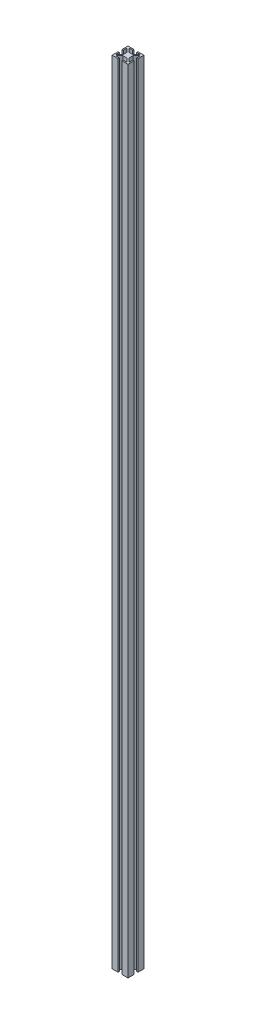
SolidWorks part; units mm, degrees
ref_plane "Plan de face" through (0, 0, 0) normal (0, 0, 1) x (1, 0, 0)
ref_plane "Plan de dessus" through (0, 0, 0) normal (0, 1, 0) x (1, 0, 0)
ref_plane "Plan de droite" through (0, 0, 0) normal (1, 0, 0) x (0, 0, -1)
sketch "Esquisse1" plane through (0, 0, 0) normal (0, 1, 0) x (1, 0, 0)
  line L0 (6.1245, 16.1036) -> (30.6226, 16.1036) construction
  line L6 (-11.5924, 0) -> (12.1076, 0) construction
  line L7 (0, 12.3466) -> (0, -12.7449) construction
  line L12 (-10, -10) -> (10, 10) construction
  line L59 (-10, -2.5) -> (-10, -10)
  line L60 (-10, -2.5) -> (-8.5, -2.5)
  line L69 (-8.5, -2.5) -> (-8.5, -6.2322)
  line L70 (-7.6464, -6.5858) -> (-3.75, -2.6893)
  line L73 (-6.5858, -7.6464) -> (-2.6893, -3.75)
  line L74 (-2.5, -8.5) -> (-6.2322, -8.5)
  line L75 (-2.5, -10) -> (-2.5, -8.5)
  line L76 (-2.5, -10) -> (-10, -10)
  line L77 (-2.5, 10) -> (-2.5, 8.5)
  line L78 (-2.5, 10) -> (-10, 10)
  line L79 (-10, 2.5) -> (-10, 10)
  line L80 (-10, 2.5) -> (-8.5, 2.5)
  line L81 (-8.5, 2.5) -> (-8.5, 6.2322)
  line L82 (-7.6464, 6.5858) -> (-3.75, 2.6893)
  line L83 (-6.5858, 7.6464) -> (-2.6893, 3.75)
  line L84 (-2.5, 8.5) -> (-6.2322, 8.5)
  line L85 (10, 2.5) -> (8.5, 2.5)
  line L86 (10, 2.5) -> (10, 10)
  line L87 (2.5, 10) -> (10, 10)
  line L88 (2.5, 10) -> (2.5, 8.5)
  line L89 (2.5, 8.5) -> (6.2322, 8.5)
  line L90 (6.5858, 7.6464) -> (2.6893, 3.75)
  line L91 (7.6464, 6.5858) -> (3.75, 2.6893)
  line L92 (8.5, 2.5) -> (8.5, 6.2322)
  line L93 (2.5, -10) -> (2.5, -8.5)
  line L94 (2.5, -10) -> (10, -10)
  line L95 (10, -2.5) -> (10, -10)
  line L96 (10, -2.5) -> (8.5, -2.5)
  line L97 (8.5, -2.5) -> (8.5, -6.2322)
  line L98 (7.6464, -6.5858) -> (3.75, -2.6893)
  line L99 (6.5858, -7.6464) -> (2.6893, -3.75)
  line L100 (2.5, -8.5) -> (6.2322, -8.5)
  line L101 (-3.75, 2.6893) -> (-3.75, -2.6893)
  line L102 (-2.6893, -3.75) -> (2.6893, -3.75)
  line L103 (-2.6893, 3.75) -> (2.6893, 3.75)
  line L104 (3.75, 2.6893) -> (3.75, -2.6893)
  arc A0 (-8.5, 6.2322) -> (-7.6464, 6.5858) centre (-8, 6.2322) cw
  arc A1 (-8.5, -6.2322) -> (-7.6464, -6.5858) centre (-8, -6.2322) ccw
  arc A2 (-6.5858, -7.6464) -> (-6.2322, -8.5) centre (-6.2322, -8) ccw
  arc A3 (6.5858, -7.6464) -> (6.2322, -8.5) centre (6.2322, -8) cw
  arc A4 (8.5, -6.2322) -> (7.6464, -6.5858) centre (8, -6.2322) cw
  arc A5 (7.6464, 6.5858) -> (8.5, 6.2322) centre (8, 6.2322) cw
  arc A6 (6.2322, 8.5) -> (6.5858, 7.6464) centre (6.2322, 8) cw
  arc A7 (-6.5858, 7.6464) -> (-6.2322, 8.5) centre (-6.2322, 8) cw
  point P7 (-2.5, -9.25)
  point P8 (2.5, -9.25)
  point P15 (-8.5, -7.4393)
  point P51 (0, 0)
  point P52 (-7.4393, -8.5)
  dimension "D2" = 5
  dimension "D7" = 0.5
  dimension "D1" = 20
  dimension "D3" = 4
  dimension "D4" = 7.5
  dimension "D5" = 1.5
  dimension "D6" = 1.5
extrude "Boss.-Extru.1" add sketch "Esquisse1" along normal blind 1000
